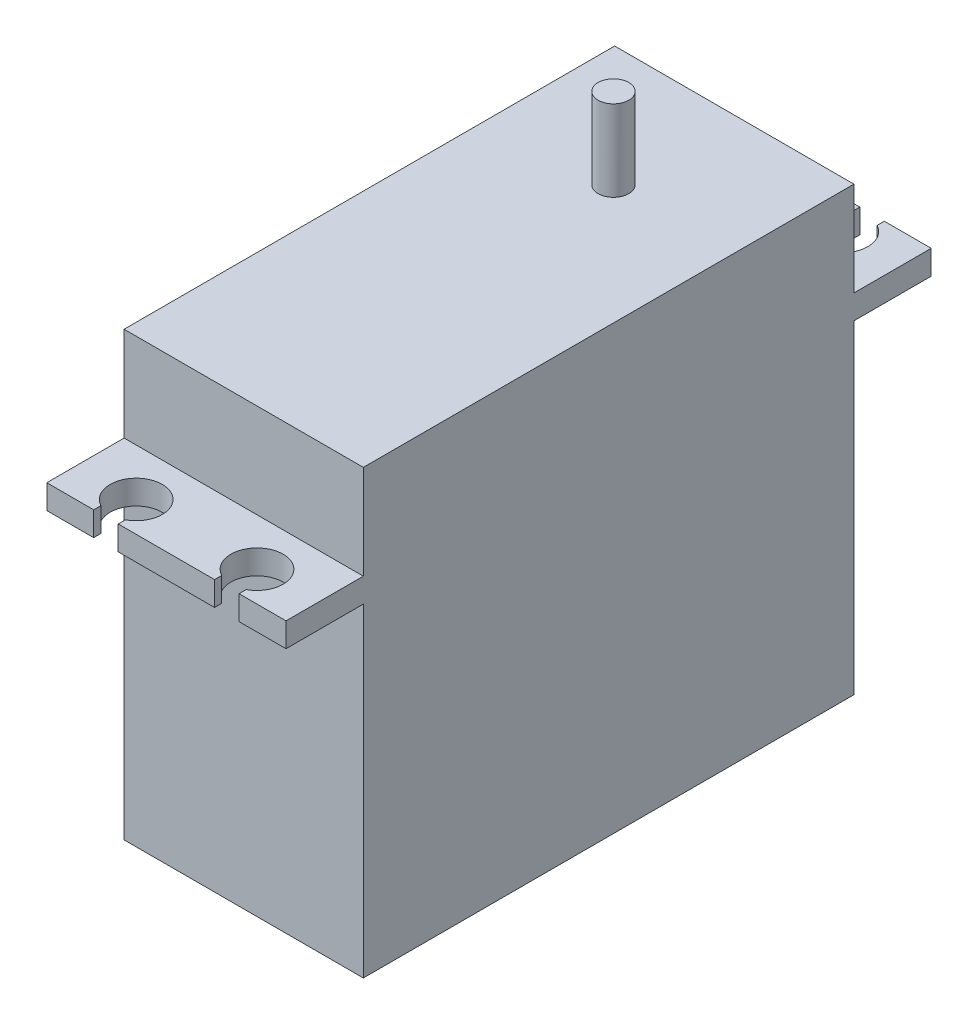
SolidWorks part; units mm, degrees
ref_plane "Front Plane" through (0, 0, 0) normal (0, 0, 1) x (1, 0, 0)
ref_plane "Top Plane" through (0, 0, 0) normal (0, 1, 0) x (1, 0, 0)
ref_plane "Right Plane" through (0, 0, 0) normal (1, 0, 0) x (0, 0, -1)
sketch "Sketch1" plane through (0, 0, 0) normal (0, 1, 0) x (1, 0, 0)
  line L1 (-9.9, -20.3) -> (9.9, -20.3)
  line L2 (-9.9, -20.3) -> (-9.9, 20.3)
  line L3 (-9.9, 20.3) -> (9.9, 20.3)
  line L4 (9.9, -20.3) -> (9.9, 20.3)
  line L5 (-9.9, -20.3) -> (9.9, 20.3) construction
  line L6 (-9.9, 20.3) -> (9.9, -20.3) construction
  point P0 (0, 0)
  dimension "D1" = 40.6
  dimension "D2" = 19.8
extrude "Boss-Extrude1" add sketch "Sketch1" along normal blind 36.6
sketch "Sketch2" plane through (0, 36.6, 0) normal (0, 1, 0) x (1, 0, 0)
  line L0 (0, 20.3) -> (0, -20.3) construction
  line L1 (9.9, 20.3) -> (-9.9, 20.3) construction
  line L2 (-9.9, -20.3) -> (9.9, -20.3) construction
  circle A0 centre (0, 10.3) radius 1.27
  dimension "D1" = 2.54
  dimension "D2" = 10
extrude "Boss-Extrude2" add sketch "Sketch2" along normal blind 6.7
sketch "Sketch3" plane through (0, 0, -20.3) normal (0, 0, -1) x (-1, 0, 0)
  line L0 (-9.9, 36.6) -> (-9.9, 0) construction
  line L1 (-9.9, 28.8) -> (9.9, 28.8)
  line L2 (-9.9, 28.8) -> (-9.9, 26.8)
  line L3 (-9.9, 26.8) -> (9.9, 26.8)
  line L4 (9.9, 28.8) -> (9.9, 26.8)
  line L5 (9.9, 36.6) -> (9.9, 0) construction
  line L7 (-9.9, 0) -> (9.9, 0) construction
  dimension "D1" = 26.8
  dimension "D2" = 2
extrude "Boss-Extrude3" add sketch "Sketch3" along normal blind 6.4
sketch "Sketch4" plane through (0, 0, 20.3) normal (0, 0, 1) x (1, 0, 0)
  line L0 (-9.9, 36.6) -> (-9.9, 0) construction
  line L1 (-9.9, 28.8) -> (9.9, 28.8)
  line L2 (-9.9, 28.8) -> (-9.9, 26.8)
  line L3 (-9.9, 26.8) -> (9.9, 26.8)
  line L4 (9.9, 28.8) -> (9.9, 26.8)
  line L5 (9.9, 36.6) -> (9.9, 0) construction
  line L6 (-9.9, 0) -> (9.9, 0) construction
  dimension "D1" = 26.8
  dimension "D2" = 2
extrude "Boss-Extrude4" add sketch "Sketch4" along normal blind 6.4
sketch "Sketch5" plane through (0, 36.6, 0) normal (0, 1, 0) x (1, 0, 0)
  line L0 (-6.016, 26.105) -> (-6.016, 26.7)
  line L1 (-5, -24.2) -> (5, -24.2) construction
  line L2 (-5, -24.2) -> (-5, 24.2) construction
  line L3 (-5, 24.2) -> (5, 24.2) construction
  line L4 (5, -24.2) -> (5, 24.2) construction
  line L5 (-5, -24.2) -> (5, 24.2) construction
  line L6 (-5, 24.2) -> (5, -24.2) construction
  line L7 (-9.9, 26.7) -> (9.9, 26.7) construction
  line L8 (-9.9, 26.7) -> (-9.9, -26.7) construction
  line L9 (-9.9, -26.7) -> (9.9, -26.7) construction
  line L10 (9.9, 26.7) -> (9.9, -26.7) construction
  line L11 (-3.984, 26.105) -> (-3.984, 26.7)
  line L12 (3.984, 26.105) -> (3.984, 26.7)
  line L13 (6.016, 26.105) -> (6.016, 26.7)
  line L14 (-6.016, -26.105) -> (-6.016, -26.7)
  line L15 (-3.984, -26.105) -> (-3.984, -26.7)
  line L16 (3.984, -26.105) -> (3.984, -26.7)
  line L17 (6.016, -26.105) -> (6.016, -26.7)
  line L18 (-6.016, -26.7) -> (-3.984, -26.7)
  line L19 (3.984, -26.7) -> (6.016, -26.7)
  line L20 (-6.016, 26.7) -> (-3.984, 26.7)
  line L21 (3.984, 26.7) -> (6.016, 26.7)
  arc A0 (-6.016, 26.105) -> (-3.984, 26.105) centre (-5, 24.2) ccw
  arc A1 (3.984, 26.105) -> (6.016, 26.105) centre (5, 24.2) ccw
  arc A2 (-3.984, -26.105) -> (-6.016, -26.105) centre (-5, -24.2) ccw
  arc A3 (6.016, -26.105) -> (3.984, -26.105) centre (5, -24.2) ccw
  point P0 (0, 0)
  dimension "D3" = 4.318
  dimension "D1" = 48.4
  dimension "D2" = 10
  dimension "D4" = 2.032
extrude "Cut-Extrude1" cut sketch "Sketch5" against normal through all
